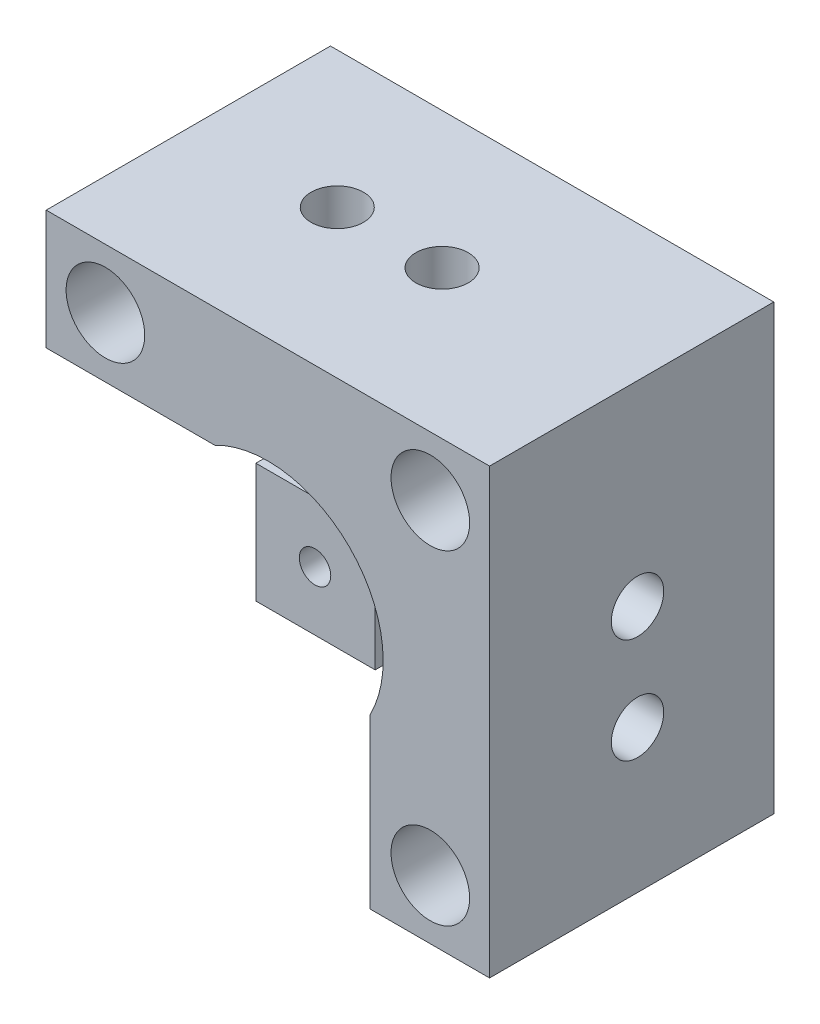
SolidWorks part; units mm, degrees
ref_plane "Front Plane" through (0, 0, 0) normal (0, 0, 1) x (1, 0, 0)
ref_plane "Top Plane" through (0, 0, 0) normal (0, 1, 0) x (1, 0, 0)
ref_plane "Right Plane" through (0, 0, 0) normal (1, 0, 0) x (0, 0, -1)
sketch "Sketch1" plane through (0, 0, 0) normal (0, 0, 1) x (1, 0, 0)
  line L8 (-14.15, -21.15) -> (14.15, -21.15)
  line L9 (14.15, -21.15) -> (21.15, -14.15)
  line L10 (21.15, -14.15) -> (21.15, 14.15)
  line L11 (21.15, 14.15) -> (14.15, 21.15)
  line L12 (14.15, 21.15) -> (-14.15, 21.15)
  line L13 (-14.15, 21.15) -> (-21.15, 14.15)
  line L14 (-21.15, 14.15) -> (-21.15, -14.15)
  line L15 (-21.15, -14.15) -> (-14.15, -21.15)
  line L16 (-21.15, -21.15) -> (21.15, -21.15)
  line L18 (21.15, -21.15) -> (21.15, 21.15)
  line L20 (21.15, 21.15) -> (-21.15, 21.15)
  line L22 (-21.15, 21.15) -> (-21.15, -21.15)
  circle A0 centre (0, 0) radius 11 construction
  circle A1 centre (0, 0) radius 11
  circle A2 centre (-15.5, 15.5) radius 1.5 construction
  circle A3 centre (15.5, 15.5) radius 1.5 construction
  circle A4 centre (15.5, -15.5) radius 1.5 construction
  circle A5 centre (-15.5, -15.5) radius 1.5 construction
  circle A6 centre (-15.5, 15.5) radius 1.5
  circle A7 centre (15.5, 15.5) radius 1.5
  circle A8 centre (15.5, -15.5) radius 1.5
  circle A9 centre (-15.5, -15.5) radius 1.5
  dimension "D1" = 0
extrude "Boss-Extrude1" add sketch "Sketch1" along normal up to surface (27.12 mm away)
sketch "Sketch2" plane through (0, -21.15, 0) normal (0, -1, 0) x (1, 0, 0)
  line L0 (-9.7611, 27.12) -> (-9.7611, 3)
  line L1 (21.15, 27.12) -> (-21.15, 27.12) construction
  line L2 (-9.7611, 3) -> (9.7624, 3)
  line L3 (9.7624, 3) -> (9.7624, 27.12)
  line L4 (9.7624, 27.12) -> (-9.7611, 27.12)
  line L11 (-4.8339, 11.4) -> (-6.7611, 11.4)
  line L12 (-6.7611, 11.4) -> (-6.7611, 5.05)
  line L13 (-6.7611, 5.05) -> (-4.8339, 5.05)
  line L14 (-4.8339, 5.05) -> (-4.8339, 11.4)
  line L15 (-4.8339, 11.4) -> (-6.7611, 11.4) construction
  line L16 (-6.7611, 11.4) -> (-6.7611, 5.05) construction
  line L17 (-6.7611, 5.05) -> (-4.8339, 5.05) construction
  line L18 (-4.8339, 5.05) -> (-4.8339, 11.4) construction
  line L19 (13.7266, 11.4) -> (6.7624, 11.4)
  line L20 (13.7266, 5.05) -> (13.7266, 11.4)
  line L21 (6.7624, 5.05) -> (13.7266, 5.05)
  line L22 (6.7624, 11.4) -> (6.7624, 5.05)
  line L25 (-21.15, 0) -> (21.15, 0) construction
  line L26 (6.7624, 11.4) -> (6.7624, 5.05) construction
  dimension "D5" = 3
  dimension "D1" = 0
  dimension "D3" = 3
  dimension "D4" = 3
  dimension "D2" = 0
extrude "Cut-Extrude1" cut sketch "Sketch2" against normal up to next contours L3 L4 L0 L2
sketch "Sketch3" plane through (0, 0, 27.12) normal (0, 0, 1) x (1, 0, 0)
  circle A0 centre (15.5, 15.5) radius 3.75
  circle A1 centre (15.5, -15.5) radius 3.75
  circle A2 centre (-15.5, 15.5) radius 3.75
  circle A3 centre (-15.5, -15.5) radius 12.2465
  dimension "D1" = 7.5
extrude "Cut-Extrude2" cut sketch "Sketch3" against normal blind 20
sketch "Sketch4" plane through (0, 21.15, 0) normal (0, 1, 0) x (1, 0, 0)
  line L0 (0, 0) -> (0, -35.7016) construction
  line L2 (21.15, 0) -> (-21.15, 0) construction
  line L3 (-7.5, -13) -> (2.5, -13) construction
  circle A0 centre (-7.5, -13) radius 2.5
  circle A1 centre (2.5, -13) radius 2.5
  dimension "D1" = 5
  dimension "D2" = 7.5
  dimension "D3" = 13
  dimension "D4" = 10
extrude "Cut-Extrude3" cut sketch "Sketch4" against normal through all
ref_plane "Plane1" through (0, 0, 0) normal (-0.7071, 0.7071, 0) x (0, 0, 1)
sketch "Sketch6" plane through (0, 21.15, 0) normal (0, 1, 0) x (1, 0, 0)
  circle A14 centre (2.5, -13) radius 4
  circle A15 centre (2.5, -13) radius 4
  circle A17 centre (-7.5, -13) radius 4
  circle A18 centre (-7.5, -13) radius 4
  dimension "D1" = 1.5
  dimension "D2" = 1.5
extrude "Cut-Extrude4" cut sketch "Sketch6" against normal through all from offset 4 contours A15 offset against normal yes
mirror "Mirror1" about plane through (0, 0, 0) normal (-0.7071, 0.7071, 0) of "Cut-Extrude4", "Cut-Extrude1", "Cut-Extrude3"
